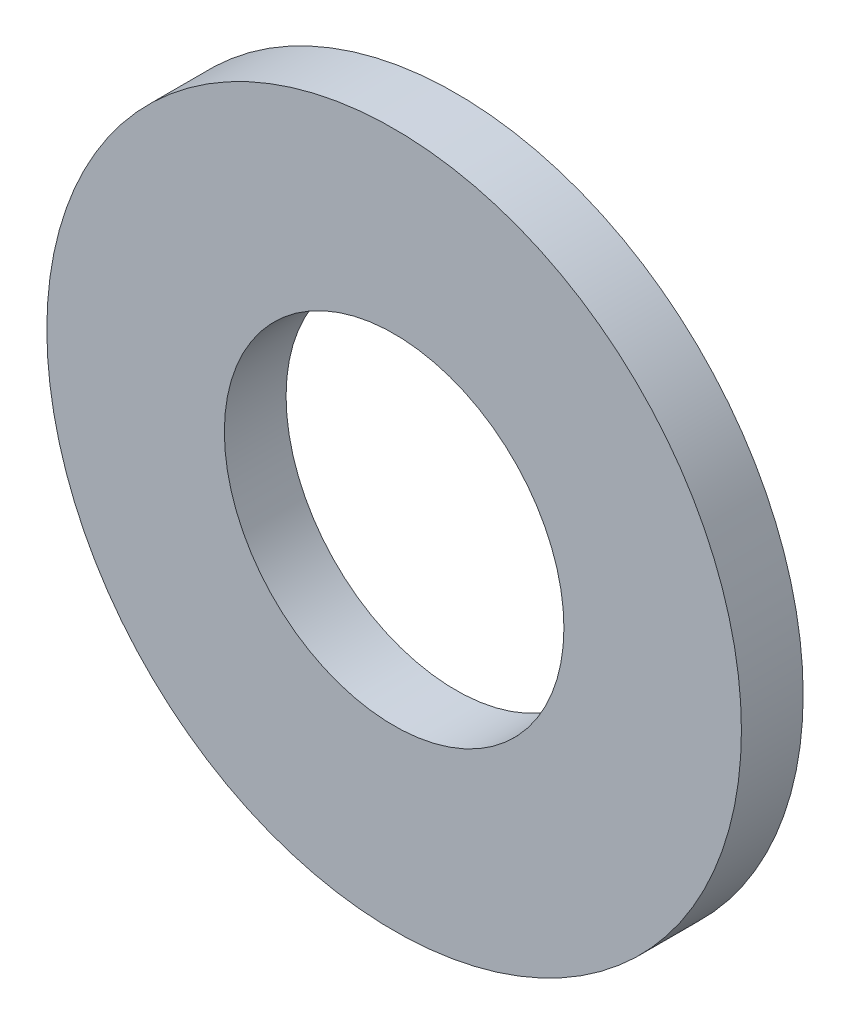
SolidWorks part; units mm, degrees
ref_plane "Front Plane" through (0, 0, 0) normal (0, 0, 1) x (1, 0, 0)
ref_plane "Top Plane" through (0, 0, 0) normal (0, 1, 0) x (1, 0, 0)
ref_plane "Right Plane" through (0, 0, 0) normal (1, 0, 0) x (0, 0, -1)
ref_plane "Plane1" through (0, 0, 0) normal (0, -1, 0) x (1, 0, 0)
sketch "Sketch1" plane through (0, 0, 0) normal (0, -1, 0) x (1, 0, 0)
  line L0 (4.5, 0) -> (4.5, 0.8)
  line L1 (4.5, 0.8) -> (2.2, 0.8)
  line L2 (2.2, 0.8) -> (2.2, 0)
  line L3 (2.2, 0) -> (4.5, 0)
  line L4 (0, 0.8) -> (0, 0) construction
revolve "Revolve1" add sketch "Sketch1" angle 360 about L4
